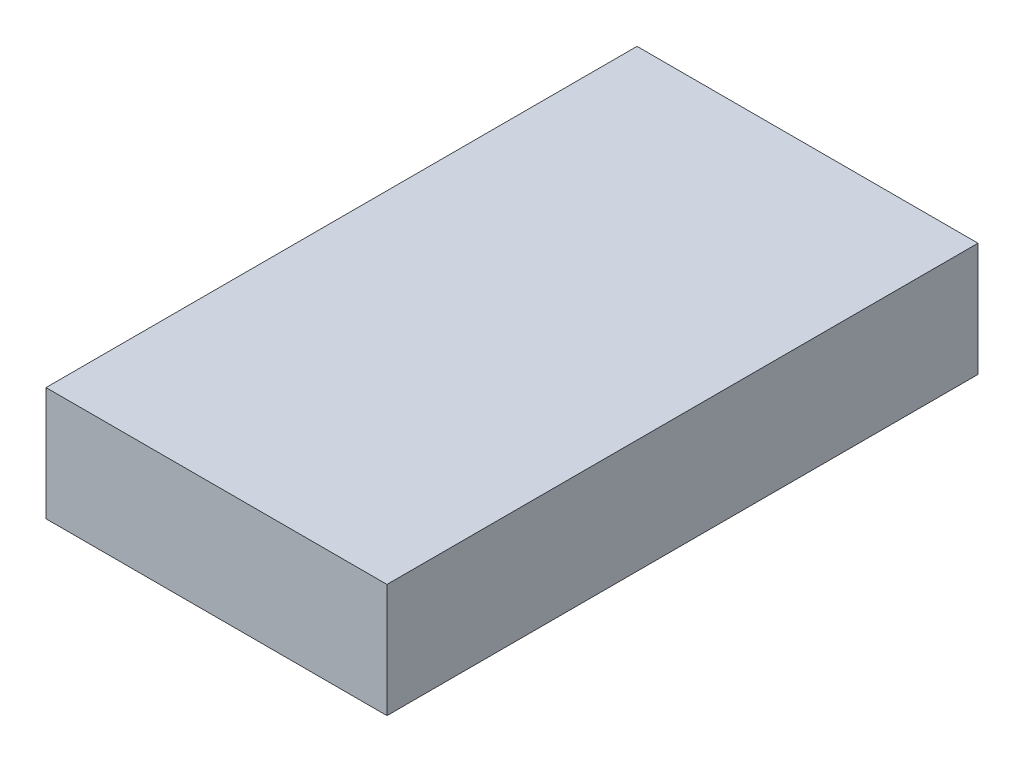
SolidWorks part; units mm, degrees
ref_plane "Спереди" through (0, 0, 0) normal (0, 0, 1) x (1, 0, 0)
ref_plane "Сверху" through (0, 0, 0) normal (0, 1, 0) x (1, 0, 0)
ref_plane "Справа" through (0, 0, 0) normal (1, 0, 0) x (0, 0, -1)
sketch "Эскиз1" plane through (0, 0, 0) normal (0, 1, 0) x (1, 0, 0)
  line L1 (-69.5642, 513.9097) -> (230.4358, 513.9097)
  line L2 (-69.5642, 513.9097) -> (-69.5642, -6.0903)
  line L3 (-69.5642, -6.0903) -> (230.4358, -6.0903)
  line L4 (230.4358, 513.9097) -> (230.4358, -6.0903)
extrude "Бобышка-Вытянуть1" add sketch "Эскиз1" along normal blind 100
